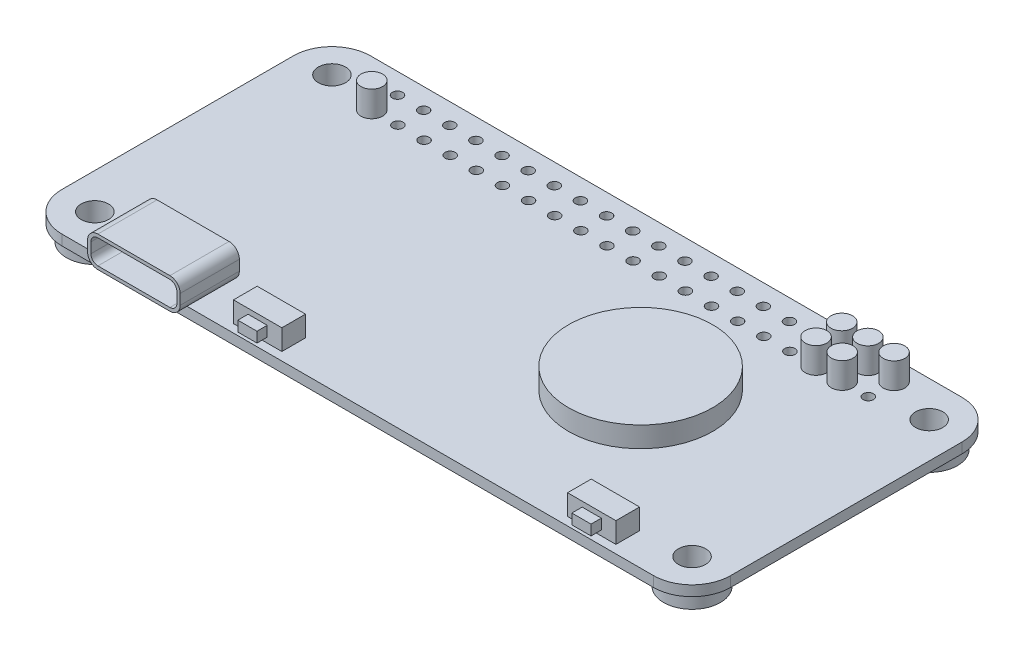
SolidWorks part; units mm, degrees
ref_plane "Front Plane" through (0, 0, 0) normal (0, 0, 1) x (1, 0, 0)
ref_plane "Top Plane" through (0, 0, 0) normal (0, 1, 0) x (1, 0, 0)
ref_plane "Right Plane" through (0, 0, 0) normal (1, 0, 0) x (0, 0, -1)
sketch "Sketch1" plane through (0, 0, 0) normal (0, 1, 0) x (1, 0, 0)
  line L1 (-28.75, 15) -> (28.75, 15)
  line L2 (-32.5, 11.25) -> (-32.5, -11.25)
  line L3 (-28.75, -15) -> (28.75, -15)
  line L4 (32.5, 11.25) -> (32.5, -11.25)
  line L5 (-32.5, 15) -> (32.5, -15) construction
  line L6 (-32.5, -15) -> (32.5, 15) construction
  arc A0 (-32.5, -11.25) -> (-28.75, -15) centre (-28.75, -11.25) ccw
  arc A1 (28.75, -15) -> (32.5, -11.25) centre (28.75, -11.25) ccw
  arc A2 (28.75, 15) -> (32.5, 11.25) centre (28.75, 11.25) cw
  arc A3 (-28.75, 15) -> (-32.5, 11.25) centre (-28.75, 11.25) ccw
  point P0 (0, 0)
  dimension "D3" = 3.75
  dimension "D1" = 65
  dimension "D2" = 30
extrude "Boss-Extrude1" add sketch "Sketch1" along normal blind 1 contours L1 A2 L4 A1 L3 A0 L2 A3
sketch "Sketch2" plane through (0, 1, 0) normal (0, 1, 0) x (1, 0, 0)
  line L0 (0, 15) -> (0, -15) construction
  line L1 (-28.75, 15) -> (28.75, 15) construction
  line L2 (-28.75, -15) -> (28.75, -15) construction
  line L3 (-32.5, 0) -> (32.5, 0) construction
  line L4 (-32.5, 11.25) -> (-32.5, -11.25) construction
  line L5 (32.5, 11.25) -> (32.5, -11.25) construction
  circle A0 centre (-29.025, 11.525) radius 1.325
  circle A2 centre (29.025, 11.525) radius 1.325
  circle A3 centre (29.025, -11.525) radius 1.325
  circle A4 centre (-29.025, -11.525) radius 1.325
  dimension "D1" = 2.65
  dimension "D2" = 2.15
  dimension "D3" = 2.15
extrude "Cut-Extrude1" cut sketch "Sketch2" against normal through all
sketch "Sketch3" plane through (0, 1, 0) normal (0, 1, 0) x (1, 0, 0)
  line L0 (-24.128, 13) -> (-24.128, 10.5) construction
  line L3 (-28.75, 15) -> (28.75, 15) construction
  line L5 (-32.5, 11.25) -> (-32.5, -11.25) construction
  circle A0 centre (-24.128, 13) radius 0.5
  circle A1 centre (-24.128, 10.5) radius 0.5
  dimension "D1" = 1
  dimension "D3" = 1.5
  dimension "D4" = 7.872
  dimension "D2" = 2.5
extrude "Cut-Extrude2" cut sketch "Sketch3" against normal through all
pattern_linear "LPattern1" count 20 spacing 2.54 along (1, 0, 0) of "Cut-Extrude2"
sketch "Sketch15" plane through (0, 0, 15) normal (0, 0, 1) x (1, 0, 0)
  line L0 (-28.75, 1) -> (28.75, 1) construction
  line L2 (-24, 4) -> (-17, 4)
  line L3 (-25, 3) -> (-25, 2)
  line L4 (-24, 1) -> (-17, 1)
  line L5 (-16, 3) -> (-16, 2)
  line L6 (-32.5, 1) -> (-32.5, 0) construction
  line L9 (15.325, 0) -> (15.325, 5.5788) construction
  line L10 (-28.75, 0) -> (28.75, 0) construction
  arc A0 (-17, 4) -> (-16, 3) centre (-17, 3) cw
  arc A1 (-17, 1) -> (-16, 2) centre (-17, 2) ccw
  arc A2 (-25, 2) -> (-24, 1) centre (-24, 2) ccw
  arc A3 (-24, 4) -> (-25, 3) centre (-24, 3) ccw
  point P10 (-16, 4)
  point P13 (-16, 1)
  point P18 (-25, 4)
  dimension "D4" = 1
  dimension "D1" = 9
  dimension "D2" = 3
  dimension "D3" = 7.5
extrude "Boss-Extrude6" add sketch "Sketch15" along normal blind 1.25 and the other way blind 4.5
sketch "Sketch16" plane through (0, 0, 16.25) normal (0, 0, 1) x (1, 0, 0)
  line L4 (-17, 3.68) -> (-24, 3.68)
  line L5 (-17, 3.68) -> (-24, 3.68)
  line L6 (-24.68, 3) -> (-24.68, 2)
  line L7 (-24.68, 3) -> (-24.68, 2)
  line L8 (-24, 1.32) -> (-17, 1.32)
  line L9 (-24, 1.32) -> (-17, 1.32)
  line L10 (-16.32, 2) -> (-16.32, 3)
  line L11 (-16.32, 2) -> (-16.32, 3)
  arc A4 (-16.32, 3) -> (-17, 3.68) centre (-17, 3) ccw
  arc A5 (-16.32, 3) -> (-17, 3.68) centre (-17, 3) ccw
  arc A6 (-24, 3.68) -> (-24.68, 3) centre (-24, 3) ccw
  arc A7 (-24, 3.68) -> (-24.68, 3) centre (-24, 3) ccw
  arc A8 (-24.68, 2) -> (-24, 1.32) centre (-24, 2) ccw
  arc A9 (-24.68, 2) -> (-24, 1.32) centre (-24, 2) ccw
  arc A10 (-17, 1.32) -> (-16.32, 2) centre (-17, 2) ccw
  arc A11 (-17, 1.32) -> (-16.32, 2) centre (-17, 2) ccw
  dimension "D2" = 0.32
extrude "Cut-Extrude9" cut sketch "Sketch16" against normal blind 5.25
sketch "草图1" plane through (0, 1, 0) normal (0, 1, 0) x (1, 0, 0)
  line L1 (-12.87, -11.9) -> (-8.17, -11.9)
  line L2 (-12.87, -11.9) -> (-12.87, -14.2)
  line L3 (-12.87, -14.2) -> (-8.17, -14.2)
  line L4 (-8.17, -11.9) -> (-8.17, -14.2)
  line L5 (-28.75, -15) -> (-24, -15) construction
  line L6 (-16, -10.5) -> (-16, -16.25) construction
  line L7 (32.5, 11.25) -> (32.5, -11.25) construction
  line L8 (24.3, -11.9) -> (19.6, -11.9)
  line L9 (24.3, -11.9) -> (24.3, -14.2)
  line L10 (24.3, -14.2) -> (19.6, -14.2)
  line L11 (19.6, -11.9) -> (19.6, -14.2)
  dimension "D1" = 4.7
  dimension "D2" = 2.3
  dimension "D3" = 3.13
  dimension "D4" = 0.8
  dimension "D5" = 8.2
extrude "凸台-拉伸1" add sketch "草图1" along normal blind 2
sketch "草图2" plane through (0, 0, 14.2) normal (0, 0, 1) x (1, 0, 0)
  line L0 (-12.87, 3) -> (-8.17, 3) construction
  line L5 (-11.45, 2.5) -> (-9.59, 2.5)
  line L6 (-11.45, 2.5) -> (-11.45, 1.5)
  line L7 (-11.45, 1.5) -> (-9.59, 1.5)
  line L8 (-9.59, 2.5) -> (-9.59, 1.5)
  line L9 (-11.45, 2.5) -> (-9.59, 1.5) construction
  line L10 (-11.45, 1.5) -> (-9.59, 2.5) construction
  line L11 (-8.17, 3) -> (-8.17, 1) construction
  line L12 (19.6, 3) -> (24.3, 3) construction
  line L13 (21.02, 2.5) -> (22.88, 2.5)
  line L14 (21.02, 2.5) -> (21.02, 1.5)
  line L15 (21.02, 1.5) -> (22.88, 1.5)
  line L16 (22.88, 2.5) -> (22.88, 1.5)
  line L17 (21.02, 2.5) -> (22.88, 1.5) construction
  line L18 (21.02, 1.5) -> (22.88, 2.5) construction
  line L19 (24.3, 3) -> (24.3, 1) construction
  point P0 (-10.52, 2)
  point P5 (21.95, 2)
  point P8 (-10.52, 3)
  point P12 (-8.17, 2)
  point P16 (0, 0)
  point P19 (21.95, 3)
  point P20 (0, 0)
  point P23 (24.3, 2)
  dimension "D1" = 1.86
  dimension "D2" = 1
extrude "凸台-拉伸2" add sketch "草图2" along normal blind 1
sketch "草图9" plane through (0, 0, 0) normal (0, -1, 0) x (1, 0, 0)
  circle A0 centre (29.025, 11.525) radius 2.75
  circle A1 centre (29.025, -11.525) radius 2.75
  circle A2 centre (-29.025, 11.525) radius 2.75
  circle A3 centre (-29.025, -11.525) radius 2.75
  circle A4 centre (29.025, 11.525) radius 1.325 construction
  circle A5 centre (29.025, -11.525) radius 1.325 construction
  circle A6 centre (-29.025, 11.525) radius 1.325 construction
  circle A7 centre (-29.025, -11.525) radius 1.325 construction
  circle A8 centre (29.025, 11.525) radius 1.325
  circle A9 centre (29.025, -11.525) radius 1.325
  circle A10 centre (-29.025, 11.525) radius 1.325
  circle A11 centre (-29.025, -11.525) radius 1.325
  dimension "D1" = 5.5
extrude "凸台-拉伸8" add sketch "草图9" along normal blind 1.5
sketch "草图10" plane through (0, 1, 0) normal (0, 1, 0) x (1, 0, 0)
  circle A0 centre (24.132, 13) radius 1.05
  circle A1 centre (21.592, 13) radius 1.05
  circle A2 centre (19.052, 13) radius 1.05
  circle A3 centre (21.592, 10.5) radius 1.05
  circle A4 centre (19.052, 10.5) radius 1.05
  circle A5 centre (-24.128, 10.5) radius 1.05
  dimension "D1" = 2.1
extrude "凸台-拉伸9" add sketch "草图10" along normal blind 2.5
sketch "草图11" plane through (0, 1, 0) normal (0, -1, 0) x (1, 0, 0)
  circle A0 centre (24.132, -13) radius 0.5
  circle A1 centre (21.592, -13) radius 0.5
  circle A2 centre (21.592, -10.5) radius 0.5
  circle A3 centre (19.052, -10.5) radius 0.5
  circle A5 centre (19.052, -13) radius 0.5
  circle A7 centre (-24.128, -10.5) radius 0.5
extrude "凸台-拉伸10" add sketch "草图11" along normal blind 3
sketch "草图12" plane through (0, 1, 0) normal (0, 1, 0) x (1, 0, 0)
  line L1 (32.5, 11.25) -> (32.5, -11.25) construction
  line L2 (-28.75, 15) -> (28.75, 15) construction
  circle A0 centre (12.5, 0) radius 7
  dimension "D1" = 14
  dimension "D2" = 20
  dimension "D3" = 15
extrude "凸台-拉伸11" add sketch "草图12" along normal blind 2
